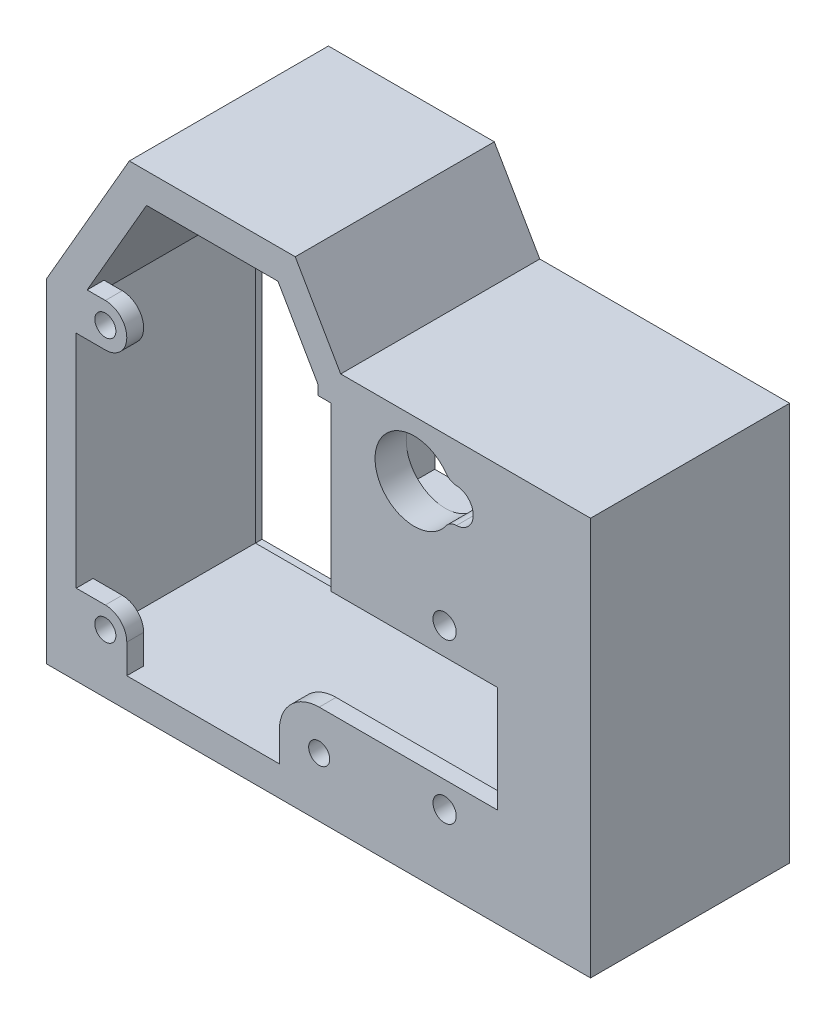
SolidWorks part; units mm, degrees
ref_plane "Front Plane" through (0, 0, 0) normal (0, 0, 1) x (1, 0, 0)
ref_plane "Top Plane" through (0, 0, 0) normal (0, 1, 0) x (1, 0, 0)
ref_plane "Right Plane" through (0, 0, 0) normal (1, 0, 0) x (0, 0, -1)
sketch "Sketch1" plane through (0, 0, 0) normal (0, 0, 1) x (1, 0, 0)
  line L1 (0, 0) -> (82, 0)
  line L2 (0, 0) -> (0, 50.2188)
  line L3 (5.6472, 60) -> (82, 60)
  line L4 (82, 0) -> (82, 60)
  line L5 (0, 50.2188) -> (50, 50.2188)
  line L6 (12.5, 71.8694) -> (12.5, 50.2188)
  line L10 (50, 50.2188) -> (37.5, 71.8694)
  line L11 (37.5, 71.8694) -> (12.5, 71.8694)
  line L12 (12.5, 71.8694) -> (0, 50.2188)
  line L13 (37.5, 28.5681) -> (43.75, 39.3934) [skipped]
  line L14 (12.5, 28.5681) -> (25, 28.5681) [skipped]
  line L15 (0, 50.2188) -> (6.25, 39.3934) [skipped]
  arc A0 (46.6506, 50.2188) -> (3.3494, 50.2188) centre (25, 50.2188) ccw construction
  dimension "D1" = 50.2188
  dimension "D4" = 21.6506
extrude "Boss-Extrude1" add sketch "Sketch1" along normal blind 30 contours L10 L11 L6 L3 | L3 L12 L5 L6 | L6 L12 L3 | L5 L10 L3 L6 | L10 L5 L2 L1 L4 L3
sketch "Sketch3" plane through (0, 0, 30) normal (0, 0, 1) x (1, 0, 0)
  line L14 (42.9094, 57.5) -> (36.0566, 69.3694)
  line L15 (36.0566, 69.3694) -> (13.9434, 69.3694)
  line L16 (13.9434, 69.3694) -> (2.5, 49.5489)
  line L17 (2.5, 49.5489) -> (2.5, 2.5)
  line L18 (2.5, 2.5) -> (79.5, 2.5)
  line L19 (79.5, 2.5) -> (79.5, 57.5)
  line L20 (79.5, 57.5) -> (42.9094, 57.5)
  line L21 (42.9094, 57.5) -> (36.0566, 69.3694)
  line L22 (36.0566, 69.3694) -> (13.9434, 69.3694)
  line L23 (13.9434, 69.3694) -> (2.5, 49.5489)
  line L24 (2.5, 49.5489) -> (2.5, 2.5)
  line L25 (2.5, 2.5) -> (79.5, 2.5)
  line L26 (79.5, 2.5) -> (79.5, 57.5)
  line L27 (79.5, 57.5) -> (42.9094, 57.5)
  dimension "D1" = 2.5
extrude "Cut-Extrude1" cut sketch "Sketch3" against normal blind 59
sketch "Sketch4" plane through (0, 0, 30) normal (0, 0, 1) x (1, 0, 0)
  line L1 (79.5, 57.5) -> (42.9094, 57.5)
  line L2 (79.5, 57.5) -> (79.5, 40.85)
  line L3 (79.5, 40.85) -> (42.9094, 40.85)
  line L4 (42.9094, 57.5) -> (42.9094, 40.85)
  dimension "D1" = 16.65
extrude "Boss-Extrude2" add sketch "Sketch4" against normal blind 9
sketch "Sketch5" plane through (0, 0, 21) normal (0, 0, -1) x (-1, 0, 0)
  line L0 (-79.5, 57.5) -> (-42.9094, 57.5) construction
  line L1 (-72.1276, 57.5) -> (-49.5276, 57.5)
  line L2 (-72.1276, 57.5) -> (-72.1276, 45.65)
  line L3 (-72.1276, 45.65) -> (-49.5276, 45.65)
  line L4 (-49.5276, 57.5) -> (-49.5276, 45.65)
  line L5 (-79.5, 40.85) -> (-79.5, 57.5) construction
  dimension "D1" = 11.85
  dimension "D2" = 7.3724
  dimension "D3" = 22.6
extrude "Cut-Extrude2" cut sketch "Sketch5" against normal blind 4.3
sketch "Sketch6" plane through (0, 0, 25.3) normal (0, 0, -1) x (-1, 0, 0)
  line L0 (-49.5276, 45.65) -> (-49.5276, 57.5) construction
  line L1 (-72.1276, 45.65) -> (-49.5276, 45.65) construction
  line L2 (-61.7276, 54.15) -> (-60.7239, 54.15)
  line L4 (-60.7239, 48.95) -> (-61.7276, 48.95)
  arc A0 (-60.7239, 48.95) -> (-60.7239, 54.15) centre (-55.4276, 51.55) ccw
  arc A1 (-61.7276, 54.15) -> (-61.7276, 48.95) centre (-61.7276, 51.55) ccw
  dimension "D2" = 11.8
  dimension "D5" = 2.6
  dimension "D1" = 5.9
  dimension "D3" = 5.9
  dimension "D4" = 12.2
extrude "Cut-Extrude3" cut sketch "Sketch6" against normal blind 10.2
sketch "Sketch8" plane through (0, 0, 30) normal (0, 0, 1) x (1, 0, 0)
  line L0 (13.9434, 69.3694) -> (2.5, 49.5489)
  line L1 (2.5, 49.5489) -> (2.5, 2.5)
  line L2 (2.5, 2.5) -> (79.5, 2.5)
  line L3 (79.5, 2.5) -> (79.5, 40.85)
  line L4 (79.5, 40.85) -> (77.5, 40.85)
  line L5 (40.9094, 55.4718) -> (42.9094, 55.4718)
  line L51 (42.9094, 55.4718) -> (42.9094, 57.5)
  line L52 (42.9094, 57.5) -> (36.0566, 69.3694)
  line L53 (36.0566, 69.3694) -> (13.9434, 69.3694)
  line L57 (40.9094, 40.85) -> (40.9094, 56.9641)
  line L58 (77.5, 4.5) -> (77.5, 40.85)
  line L59 (4.5, 4.5) -> (77.5, 4.5)
  line L60 (4.5, 49.013) -> (4.5, 4.5)
  line L61 (15.0981, 67.3694) -> (4.5, 49.013)
  line L62 (40.9094, 56.9641) -> (34.9019, 67.3694)
  line L63 (34.9019, 67.3694) -> (15.0981, 67.3694)
  line L64 (40.9094, 55.4718) -> (40.9094, 56.9641)
  line L65 (77.5, 4.5) -> (77.5, 40.85)
  line L66 (4.5, 4.5) -> (77.5, 4.5)
  line L67 (4.5, 49.013) -> (4.5, 4.5)
  line L68 (15.0981, 67.3694) -> (4.5, 49.013)
  line L69 (40.9094, 56.9641) -> (34.9019, 67.3694)
  line L70 (34.9019, 67.3694) -> (15.0981, 67.3694)
  dimension "D1" = 2
extrude "Boss-Extrude3" add sketch "Sketch8" against normal blind 27
sketch "Sketch9" plane through (0, 0, 30) normal (0, 0, 1) x (1, 0, 0)
  line L0 (77.5, 4.5) -> (4.5, 4.5) construction
  line L1 (77.5, 40.85) -> (68.0082, 40.85)
  line L2 (77.5, 40.85) -> (77.5, 4.5)
  line L3 (77.5, 4.5) -> (68.0082, 4.5)
  line L4 (68.0082, 30.9023) -> (68.0082, 14.9023)
  line L5 (0, 0) -> (82, 0) construction
  line L6 (8.89, 45.3989) -> (4.5, 45.3989)
  line L7 (0, 0) -> (0, 50.2188) construction
  line L8 (4.5, 4.5) -> (4.5, 49.013) construction
  line L9 (8.89, 51.8599) -> (6.1437, 51.8599)
  line L10 (4.5, 49.013) -> (15.0981, 67.3694) construction
  line L11 (8.89, 12.1205) -> (4.5, 12.1205)
  line L12 (12.1205, 8.89) -> (12.1205, 4.5)
  line L13 (44.3405, 14.9023) -> (41.11, 14.9023)
  line L14 (35.0977, 8.89) -> (35.0977, 4.5)
  line L15 (35.0977, 4.5) -> (44.3405, 4.5)
  line L16 (68.0082, 40.85) -> (42.9094, 40.85)
  line L18 (68.0082, 30.9023) -> (42.9094, 30.9023)
  line L19 (42.9094, 40.85) -> (42.9094, 30.9023)
  line L20 (68.0082, 4.5) -> (44.3405, 4.5)
  line L22 (68.0082, 14.9023) -> (44.3405, 14.9023)
  circle A0 centre (8.89, 8.89) radius 1.5875
  circle A1 centre (41.11, 8.89) radius 1.5875
  circle A2 centre (8.89, 48.6294) radius 1.5875
  arc A3 (8.89, 45.3989) -> (8.89, 51.8599) centre (8.89, 48.6294) ccw
  arc A4 (12.1205, 8.89) -> (8.89, 12.1205) centre (8.89, 8.89) ccw
  arc A6 (41.11, 14.9023) -> (35.0977, 8.89) centre (41.11, 8.89) ccw
  line M1 (42.9094, 40.85) -> (77.5, 40.85)
  line M2 (77.5, 40.85) -> (77.5, 4.5)
  line M3 (77.5, 4.5) -> (4.5, 4.5)
  line M4 (4.5, 4.5) -> (4.5, 49.013)
  line M5 (4.5, 49.013) -> (15.0981, 67.3694)
  dimension "D5" = 3.175
  dimension "D6" = 6.461
  dimension "D1" = 8.89
  dimension "D2" = 8.89
  dimension "D3" = 32.22
  dimension "D4" = 48.6294
  dimension "D7" = 9.4918
  dimension "D8" = 9.9477
  dimension "D9" = 10.4023
extrude "Boss-Extrude5" add sketch "Sketch9" against normal blind 2.54 contours L6 A3 L9 A2 M5 M4 | L12 A4 L11 A0 M4 M3 | L13 A6 L14 L19 L18 L4 L22 A1 M3 M2 M1
sketch "Sketch11" plane through (0, 0, 27.46) normal (0, 0, -1) x (-1, 0, 0)
  line L0 (-77.5, 4.5) -> (-4.5, 4.5) construction
  line L1 (-77.5, 4.5) -> (-35.0977, 4.5) construction
  line L2 (-77.5, 40.85) -> (-77.5, 4.5) construction
  circle A0 centre (-60.0082, 35) radius 1.7526
  circle A1 centre (-60.0082, 11) radius 1.7526
  dimension "D3" = 3.5052
  dimension "D4" = 17.4918
  dimension "D1" = 30.5
  dimension "D2" = 6.5
extrude "Cut-Extrude4" cut sketch "Sketch11" against normal blind 16
fillet "Fillet1" radius 2 2 edges at (60.7239, 48.95, 27.65) (60.7239, 54.15, 27.65)
